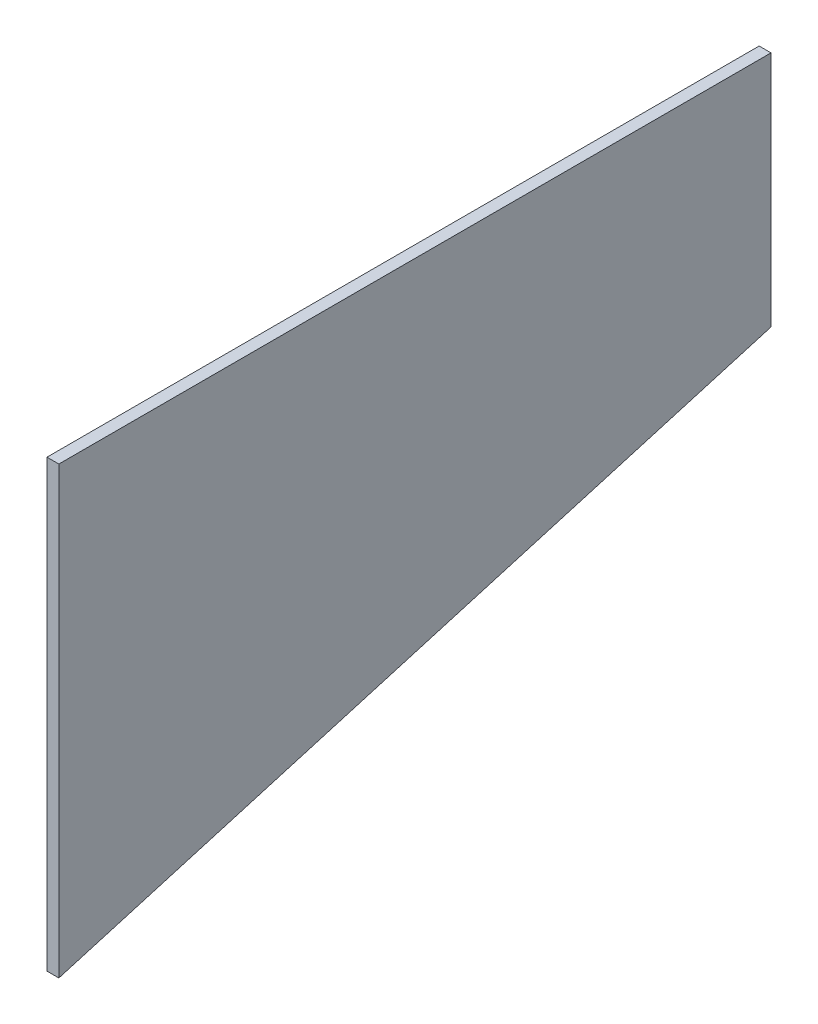
SolidWorks part; units mm, degrees
ref_plane "Front" through (0, 0, 0) normal (0, 0, 1) x (1, 0, 0)
ref_plane "Top" through (0, 0, 0) normal (0, 1, 0) x (1, 0, 0)
ref_plane "Right" through (0, 0, 0) normal (1, 0, 0) x (0, 0, -1)
sketch "Sketch2" plane through (0, 0, 0) normal (1, 0, 0) x (0, 0, -1)
  line L0 (0, -75) -> (0, 0)
  line L1 (0, 0) -> (120, 0)
  line L2 (120, 0) -> (120, -40)
  line L3 (120, -40) -> (0, -75)
  point P4 (92.7889, -20.3886)
  point P6 (25.4388, -17.0512)
  point P8 (0, 0)
  dimension "D1" = 75
  dimension "D2" = 120
  dimension "D3" = 40
extrude "Boss-Extrude1" add sketch "Sketch2" along normal blind 2
